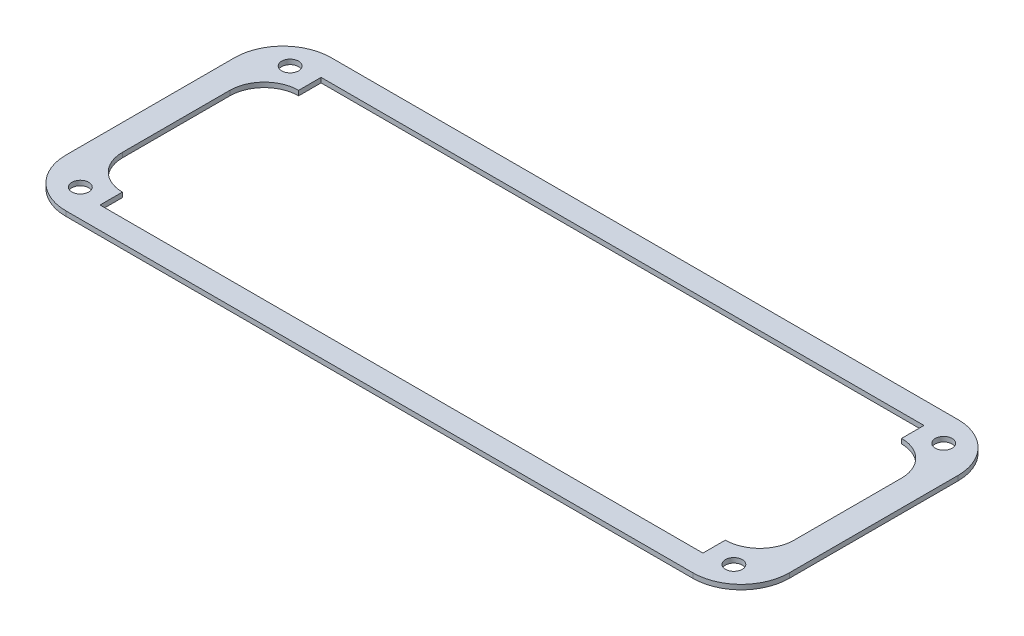
SolidWorks part; units mm, degrees
ref_plane "Front Plane" through (0, 0, 0) normal (0, 0, 1) x (1, 0, 0)
ref_plane "Top Plane" through (0, 0, 0) normal (0, 1, 0) x (1, 0, 0)
ref_plane "Right Plane" through (0, 0, 0) normal (1, 0, 0) x (0, 0, -1)
sketch "Sketch1" plane through (0, 0, 0) normal (0, 1, 0) x (1, 0, 0)
  line L0 (0, 0) -> (135.5, 43.5) construction
  line L1 (23.5794, 35.9302) -> (135.5, 0) construction
  line L2 (130.25, 40.0164) -> (130.25, 44.6667)
  line L3 (132.75, -5.75) -> (2.75, -5.75)
  line L4 (142.75, 4.25) -> (142.75, 39.25)
  line L5 (132.75, 49.25) -> (2.75, 49.25)
  line L6 (-7.25, 4.25) -> (-7.25, 39.25)
  line L7 (142.75, -5.75) -> (-7.25, 49.25) construction
  line L8 (142.75, 49.25) -> (-7.25, -5.75) construction
  line L9 (130.25, -1.1667) -> (5.25, -1.1667)
  line L10 (130.25, -1.1667) -> (130.25, 3.4836)
  line L11 (130.25, 44.6667) -> (5.25, 44.6667)
  line L12 (5.25, -1.1667) -> (5.25, 3.4797)
  line L13 (130.25, -1.1667) -> (5.25, 44.6667) construction
  line L14 (130.25, 44.6667) -> (5.25, -1.1667) construction
  line L15 (-1.8838, 10.6136) -> (-1.8838, 32.8864)
  line L17 (5.25, 40.0203) -> (5.25, 44.6667)
  line L20 (137.38, 10.6136) -> (137.38, 32.8864)
  circle A0 centre (0, 0) radius 1.75
  circle A1 centre (0, 43.5) radius 1.75
  circle A2 centre (135.5, 43.5) radius 1.75
  circle A3 centre (135.5, 0) radius 1.75
  arc A4 (132.75, -5.75) -> (142.75, 4.25) centre (132.75, 4.25) ccw
  arc A5 (2.75, -5.75) -> (-7.25, 4.25) centre (2.75, 4.25) cw
  arc A6 (142.75, 39.25) -> (132.75, 49.25) centre (132.75, 39.25) ccw
  arc A7 (2.75, 49.25) -> (-7.25, 39.25) centre (2.75, 39.25) ccw
  arc A8 (-1.8838, 10.6136) -> (5.25, 3.4797) centre (5.25, 10.6136) ccw
  arc A9 (5.25, 40.0203) -> (-1.8838, 32.8864) centre (5.25, 32.8864) ccw
  arc A10 (130.25, 3.4836) -> (137.38, 10.6136) centre (130.25, 10.6136) ccw
  arc A11 (137.38, 32.8864) -> (130.25, 40.0164) centre (130.25, 32.8864) ccw
  point P5 (67.75, 21.75)
  point P26 (67.75, 21.75)
  point P33 (5.25, 21.75)
  point P41 (130.25, 21.75)
  dimension "D1" = 3.5
  dimension "D2" = 3.5
  dimension "D4" = 3.5
  dimension "D8" = 3.5
  dimension "D11" = 10
  dimension "D13" = 7.13
  dimension "D3" = 43.5
  dimension "D5" = 135.5
  dimension "D6" = 135.5
  dimension "D7" = 43.5
  dimension "D9" = 55
  dimension "D10" = 150
  dimension "D12" = 125
extrude "Boss-Extrude1" add sketch "Sketch1" along normal blind 1
